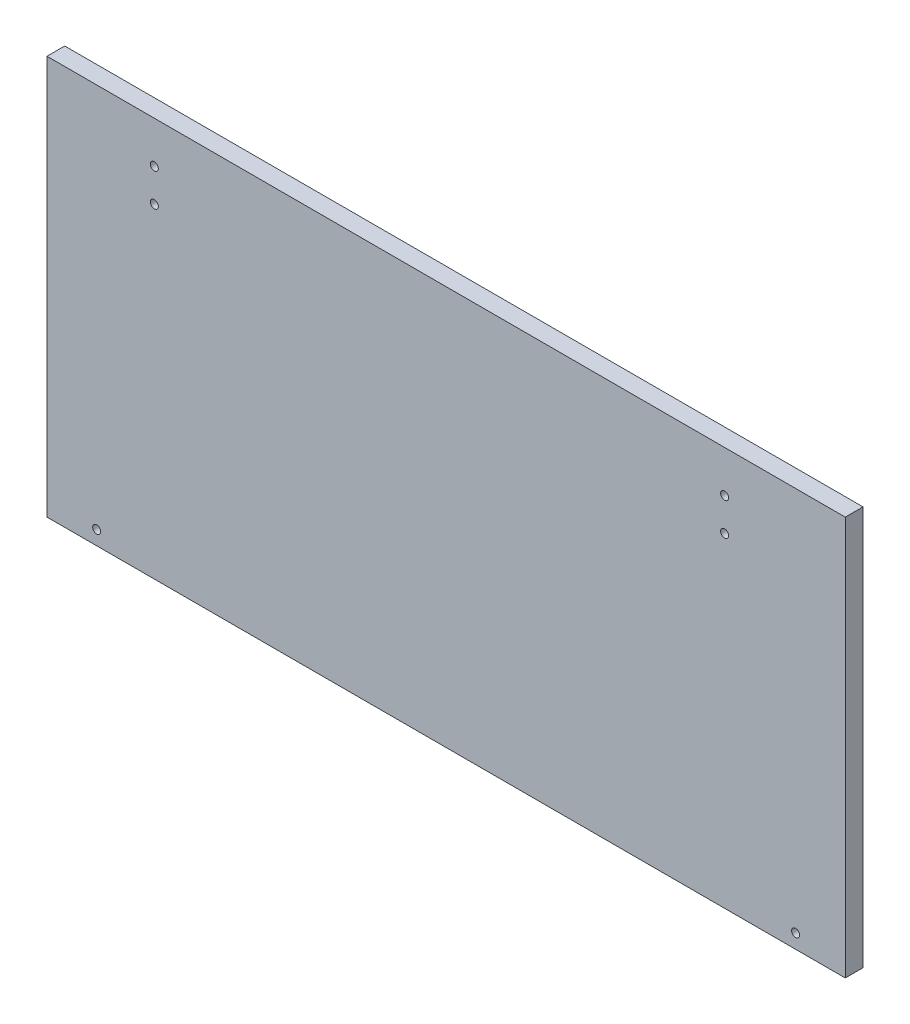
SolidWorks part; units mm, degrees
material "Multistrato di pioppo"
ref_plane "Piano frontale" through (0, 0, 0) normal (0, 0, 1) x (1, 0, 0)
ref_plane "Piano superiore" through (0, 0, 0) normal (0, 1, 0) x (1, 0, 0)
ref_plane "Piano destro" through (0, 0, 0) normal (1, 0, 0) x (0, 0, -1)
sketch "Schizzo1" plane through (0, 0, 0) normal (0, 0, 1) x (1, 0, 0)
  line L5 (-225, 112.5) -> (225, 112.5)
  line L6 (-225, 112.5) -> (-225, -112.5)
  line L7 (-225, -112.5) -> (225, -112.5)
  line L8 (225, 112.5) -> (225, -112.5)
  line L9 (-225, 112.5) -> (225, -112.5) construction
  line L10 (-225, -112.5) -> (225, 112.5) construction
  point P8 (0, 0)
  dimension "D1" = 225
  dimension "D2" = 450
extrude "Estrusione-Estrusione1" add sketch "Schizzo1" along normal blind 10
sketch "Schizzo2" plane through (0, 0, 0) normal (0, 0, -1) x (-1, 0, 0)
  circle A0 centre (-157, 89) radius 2.25
  circle A1 centre (-157, 70.5) radius 2.25
  circle A2 centre (164.5, 89) radius 2.25
  circle A3 centre (164.5, 70.5) radius 2.25
  dimension "D1" = 4.5
extrude "Taglio-Estrusione1" cut sketch "Schizzo2" against normal blind 10
sketch "Schizzo3" plane through (0, 0, 0) normal (0, 0, -1) x (-1, 0, 0)
  line L0 (197, -104.5) -> (-197, -104.5) construction
  line L1 (225, -112.5) -> (-225, -112.5) construction
  line L2 (225, 112.5) -> (225, -112.5) construction
  line L3 (-225, -112.5) -> (-225, 112.5) construction
  circle A0 centre (197, -104.5) radius 2.25
  circle A1 centre (-197, -104.5) radius 2.25
  dimension "D1" = 4.5
  dimension "D2" = 8
  dimension "D3" = 28
  dimension "D4" = 28
extrude "Taglio-Estrusione2" cut sketch "Schizzo3" against normal blind 10
